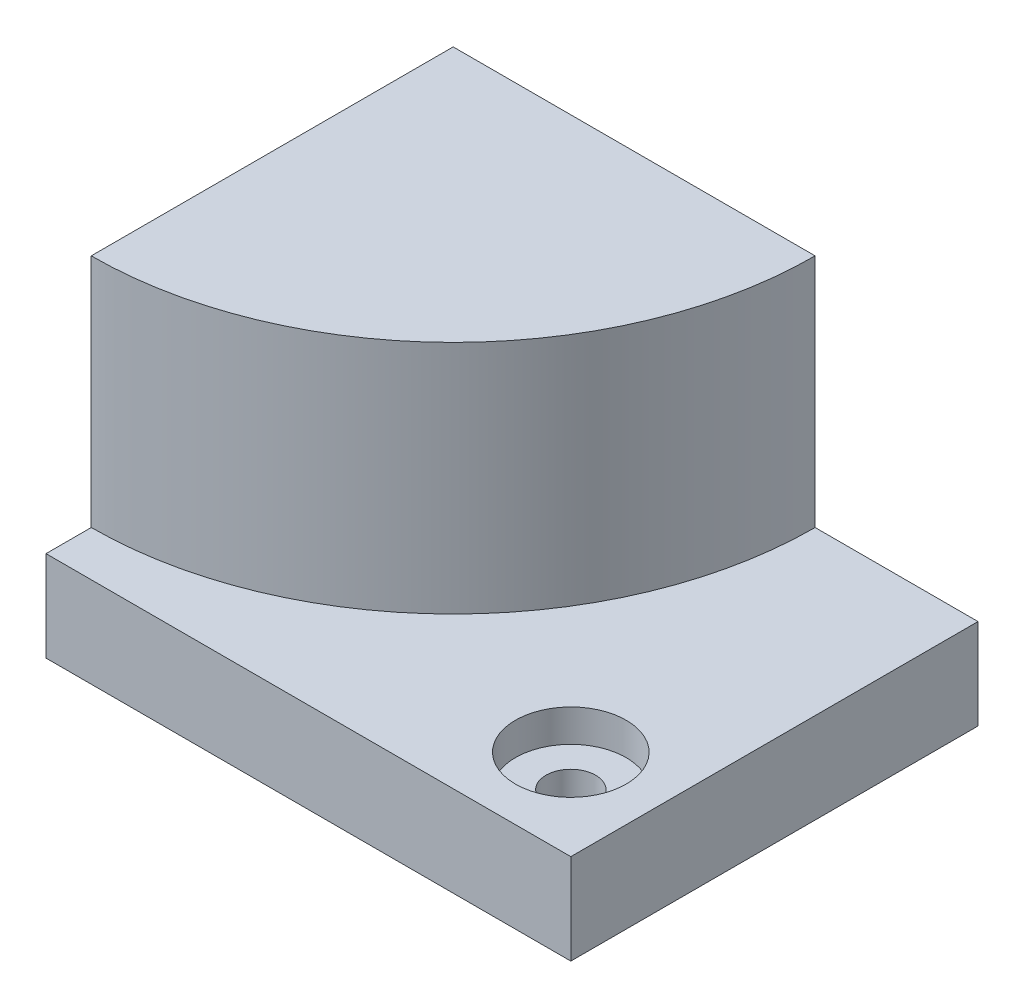
SolidWorks part; units mm, degrees
other "Markup1"
sketch "Sketch1" plane through (0, 0, 0) normal (0.5774, 0.5773, 0.5774) x (0.7071, 0, -0.7071)
sketch "Sketch2" plane through (0, 0, 0) normal (0.5774, 0.5773, 0.5774) x (0.7071, 0, -0.7071)
ref_plane "Front (z)" through (0, 0, 0) normal (0, 0, 1) x (1, 0, 0)
ref_plane "Top (y)" through (0, 0, 0) normal (0, 1, 0) x (1, 0, 0)
ref_plane "Right (x)" through (0, 0, 0) normal (1, 0, 0) x (0, 0, -1)
sketch "Sketch3" plane through (0, 0, 0) normal (0, 1, 0) x (1, 0, 0)
  line L1 (-29, -22.5) -> (29, -22.5)
  line L2 (-29, -22.5) -> (-29, 22.5)
  line L3 (-29, 22.5) -> (29, 22.5)
  line L4 (29, -22.5) -> (29, 22.5)
  line L5 (-29, -22.5) -> (29, 22.5) construction
  line L6 (-29, 22.5) -> (29, -22.5) construction
  point P0 (0, 0)
  dimension "D1" = 58
  dimension "D2" = 45
extrude "Boss-Extrude1" add sketch "Sketch3" along normal blind 10
hole_wizard "CBORE for M5 Hex Head Bolt1" positions "Sketch4" profile "Sketch5" counterbore size "M5" standard "ANSI Metric" end condition through all
sketch "Sketch4" plane through (0, 10, 0) normal (0, 1, 0) x (1, 0, 0)
  line L0 (-29, -22.5) -> (29, -22.5) construction
  line L1 (29, -22.5) -> (29, 22.5) construction
  point P0 (19, -12.5)
  dimension "D1" = 10
  dimension "D2" = 10
sketch "Sketch5" plane through (19, 10, 12.5) normal (1, 0, 0) x (0, 0, 1)
  line L0 (0, 0) -> (0, 10)
  line L1 (0, 10) -> (2.75, 10)
  line L3 (2.75, 10) -> (2.75, 3.58)
  line L4 (2.75, 3.58) -> (6.12, 3.58)
  line L5 (6.12, 3.58) -> (6.12, 0)
  line L7 (6.12, 0) -> (0, 0)
  line L11 (0, -6.35) -> (0, 107.95) construction
  dimension "Thru Hole Dia." = 5.5
  dimension "Thru Hole Depth" = 10
  dimension "C'Bore Dia." = 12.24
  dimension "C'Bore Depth" = 3.58
sketch "Sketch8" plane through (0, 10, 0) normal (0, 1, 0) x (1, 0, 0)
  line L0 (11, 22.5) -> (1, 22.5)
  line L1 (-29, -7.5) -> (-29, -17.5)
  arc A0 (-29, -7.5) -> (1, 22.5) centre (-29, 22.5) ccw
  arc A1 (-29, -17.5) -> (11, 22.5) centre (-29, 22.5) ccw
  circle A3 centre (-29, 22.5) radius 40 construction
  circle A4 centre (-29, 22.5) radius 30 construction
  point P4 (3.6891, 33.7712)
  point P9 (-5, 25)
  dimension "D1" = 60
  dimension "D2" = 10
extrude "Boss-Extrude3" add sketch "Sketch8" along normal blind 16
sketch "Sketch9" plane through (0, 26, 0) normal (0, 1, 0) x (1, 0, 0)
  line L0 (11, 22.5) -> (-29, 22.5)
  line L1 (-29, 22.5) -> (-29, -17.5)
  arc A0 (-29, -17.5) -> (11, 22.5) centre (-29, 22.5) ccw construction
  arc A1 (-29, -17.5) -> (11, 22.5) centre (-29, 22.5) ccw
extrude "Boss-Extrude4" add sketch "Sketch9" along normal blind 10
sketch "Sketch10" plane through (0, 10, 0) normal (0, 1, 0) x (1, 0, 0)
  line L0 (1, 22.5) -> (-29, 22.5) construction
  line L1 (-29, 22.5) -> (-29, -7.5) construction
  circle A0 centre (-14, 7.5) radius 2
  dimension "D1" = 4
  dimension "D2" = 15
  dimension "D3" = 15
extrude "Cut-Extrude2" cut sketch "Sketch10" against normal blind 6
